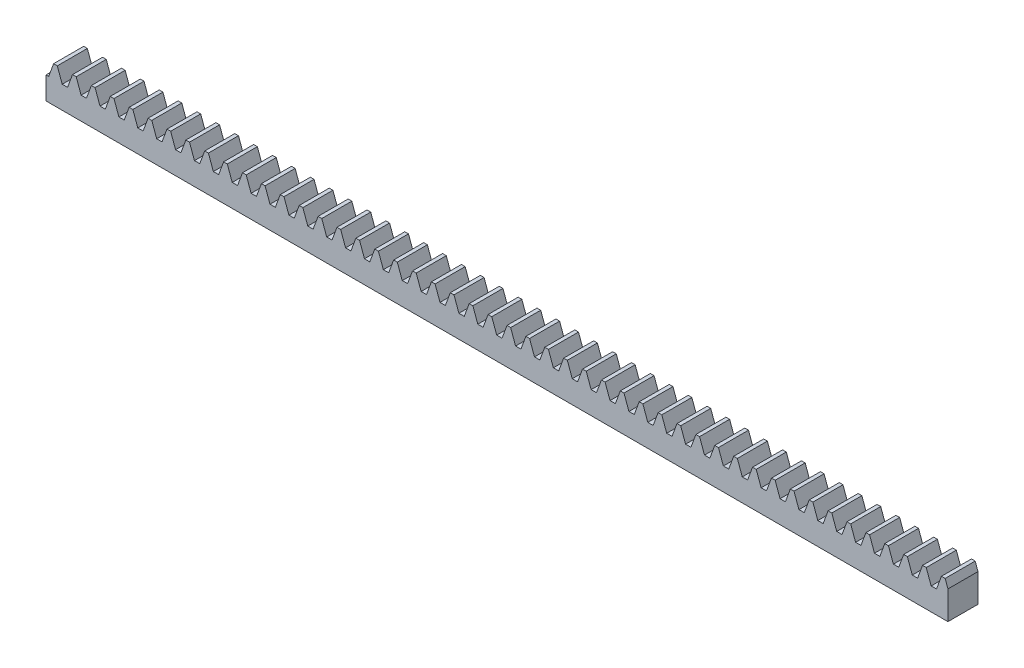
SolidWorks part; units mm, degrees
extrude "Blank" add sketch "BlankSke" against normal blind 5
sketch "BlankSke" plane through (0, 0, 0) normal (0, 0, 1) x (1, 0, 0)
  line L1 (0, 0) -> (150, 0)
  line L2 (0, 0) -> (0, 6)
  line L3 (0, 6) -> (150, 6)
  line L4 (150, 0) -> (150, 6)
  dimension "Length" = 150
  dimension "Blank_height" = 6
ref_plane "Plane1" through (0, 0, 0) normal (0, 0, 1) x (1, 0, 0)
ref_plane "Plane2" through (0, 0, 0) normal (0, 1, 0) x (1, 0, 0)
ref_plane "Plane3" through (0, 0, 0) normal (1, 0, 0) x (0, 0, -1)
sketch "HoldingSke" plane through (0, 0, 0) normal (0, 1, 0) x (1, 0, 0)
  line L0 (0, 0) -> (0.1392, 0.9903)
  line L1 (-15, 0) -> (100, 0) construction
  line L2 (0, 0) -> (-2.1039, 2.3779)
  line L3 (0, 0) -> (-11.863, 4.5341)
  line L4 (0, 0) -> (5.6657, 6.5177)
  line L5 (0, 0) -> (-23.7986, -8.8762)
  line L6 (0, 0) -> (-10.5278, -7.1032)
  line L9 (-71.009, 38.7566) -> (69.9449, 90.0596)
  line L10 (-76.2, 3.3779) -> (-71.2, 3.3779)
  line L11 (0, 0) -> (-5, 0)
  line L12 (-76.2, 101.6) -> (-76.162, 101.6)
  line L13 (24.9733, 27.94) -> (52.9518, 28.4284)
  line L14 (24.9733, 27.94) -> (24.9743, 27.94)
  line L15 (24.9733, 27.94) -> (100.4006, 29.5858)
  circle A0 centre (0, 0) radius 19.05
  circle A1 centre (0, 0) radius 2.5
  circle A2 centre (0, 0) radius 12.7
  dimension "MPH" = 5
  dimension "Diameter" = 38.1
  dimension "Num_teeth" = 49
  dimension "Pitch" = 1
  dimension "Show_teeth" = 998
  dimension "Thickness" = 12.7
  dimension "Ap" = 20
  dimension "Pitch_height" = 5
  dimension "Width" = 5
  dimension "Backlash" = 0.038
  dimension "Addendum_fac" = 1
  dimension "Dedendum_fac" = 1.25
  dimension "Clearance_fac" = 0.25
  dimension "Dedendum_add" = 0.001
  dimension "Length" = 150
  dimension "Module" = 1
sketch "TooCutSkeIll" plane through (0, 0, 0) normal (0, 0, 1) x (1, 0, 0)
  line L0 (-1.2538, 5.9737) -> (-0.5045, 3.9152)
  line L1 (-0.2687, 3.75) -> (0.2687, 3.75)
  line L2 (0.5045, 3.9152) -> (1.2538, 5.9737)
  line L3 (150, 6) -> (0, 6) construction
  line L4 (0, 0) -> (0, 64.897) construction
  line L5 (-13.208, 5) -> (12.954, 5) construction
  line L6 (0, 0) -> (150, 0) construction
  line L7 (0.8994, 5) -> (0.8994, 48.7463) construction
  line L8 (-0.8994, 5) -> (-0.8994, 48.7463) construction
  line L9 (1.2914, 6) -> (1.2914, 6.0254)
  line L10 (-1.2914, 6) -> (-1.2914, 6.0254)
  line L11 (-1.2914, 6.0254) -> (1.2914, 6.0254)
  arc A0 (0.2687, 3.75) -> (0.5045, 3.9152) centre (0.2687, 4.001) ccw
  arc A1 (-0.5045, 3.9152) -> (-0.2687, 3.75) centre (-0.2687, 4.001) ccw
  arc A2 (1.2914, 6) -> (1.2538, 5.9737) centre (1.2914, 5.96) ccw
  arc A3 (-1.2538, 5.9737) -> (-1.2914, 6) centre (-1.2914, 5.96) ccw
  dimension "Pitch_height" = 5
  dimension "Addendum_plus" = 1.0254
  dimension "Pressure_angle" = 20
  dimension "Gap_width" = 1.7988
  dimension "Dedendum" = 1.25
extrude "ToothCutIll" [suppressed] cut sketch "TooCutSkeIll" against normal through all
sketch "TooCutSkeSim" plane through (0, 0, 0) normal (0, 0, 1) x (1, 0, 0)
  line L0 (0.4444, 3.75) -> (-0.4444, 3.75)
  line L1 (1.2726, 6.0254) -> (0.4444, 3.75)
  line L2 (0, 17.4625) -> (0, 53.467) construction
  line L3 (1.2726, 6.0254) -> (-1.2726, 6.0254)
  line L6 (-1.2726, 6.0254) -> (-0.4444, 3.75)
  line L9 (-0.8994, 5) -> (0.8994, 5) construction
  line L10 (0, 0) -> (150, 0) construction
  line L11 (0.8994, 5) -> (0.8994, 53.467) construction
  line L12 (-0.8994, 5) -> (-0.8994, 53.467) construction
  dimension "Pitch_height" = 5
  dimension "Addendum_plus" = 1.0254
  dimension "Pressure_angle" = 20
  dimension "Gap_width" = 1.7988
  dimension "Dedendum" = 1.25
extrude "ToothCutSim" cut sketch "TooCutSkeSim" against normal through all
pattern_linear "TeethCuts" count 48 spacing 3.1416 along (1, 0, 0) of "ToothCutIll", "ToothCutSim"
equation "' \"Module@HoldingSke\" = 6.35"
equation "' \"Num_teeth@HoldingSke\" = 12"
equation "' \"Ap@HoldingSke\" =  20"
equation "' \"Ap@HoldingSke\" = 20"
equation "' \"Width@HoldingSke\" = 0.25 * 25.4"
equation "' \"Show_teeth@HoldingSke\" = 500"
equation "' \"Backlash@HoldingSke\" = 0.009 * 25.4"
equation "' \"Addendum_fac@HoldingSke\" = 1.0"
equation "' \"Dedendum_fac@HoldingSke\" = 1.25"
equation "' \"Dedendum_add@HoldingSke\" = 0.00005 * 25.4"
equation "' \"Clearance_fac@HoldingSke\" = 0.25"
equation "' \"Pitch_height@HoldingSke\" = 1 * 25.4"
equation "' \"Length@HoldingSke\" = 4.71 * 25.4"
equation "\"Pitch@HoldingSke\" = 1 / \"Module@HoldingSke\""
equation "\"MPH@HoldingSke\" = \"Dedendum_fac@HoldingSke\" / \"Pitch@HoldingSke\" + 2 * \"Dedendum_add@HoldingSke\" + 0.002 * 25.4"
equation "\"MPH@HoldingSke\" = ((sgn( \"MPH@HoldingSke\" - \"Pitch_height@HoldingSke\")+1)*( \"MPH@HoldingSke\" - \"Pitch_height@HoldingSke\"))/2 + \"Pitch_height@HoldingSke\""
equation "\"Blank_height@BlankSke\" = \"Pitch_height@HoldingSke\" + \"Addendum_fac@HoldingSke\"  / \"Pitch@HoldingSke\" "
equation "\"Length@BlankSke\" =  \"Length@HoldingSke\""
equation "\"Face_width@Blank\" = \"Width@HoldingSke\""
equation "\"Pressure_angle@TooCutSkeIll\" = \"Ap@HoldingSke\""
equation "\"Addendum_plus@TooCutSkeIll\" =  \"Addendum_fac@HoldingSke\"  / \"Pitch@HoldingSke\" + 0.001 *25.4"
equation "\"Dedendum@TooCutSkeIll\" = \"Dedendum_fac@HoldingSke\"  / \"Pitch@HoldingSke\""
equation "\"Pitch_height@TooCutSkeIll\" =  \"MPH@HoldingSke\""
equation "\"Gap_width@TooCutSkeIll\" = 3.14159265 / 2 / \"Pitch@HoldingSke\" + 6 * \"Backlash@HoldingSke\""
equation "\"Pressure_angle@TooCutSkeSim\" = \"Ap@HoldingSke\""
equation "\"Addendum_plus@TooCutSkeSim\" =  \"Addendum_fac@HoldingSke\"  / \"Pitch@HoldingSke\" + 0.001 * 25.4"
equation "\"Dedendum@TooCutSkeSim\" = \"Dedendum_fac@HoldingSke\"  / \"Pitch@HoldingSke\""
equation "\"Pitch_height@TooCutSkeSim\" =  \"MPH@HoldingSke\""
equation "\"Gap_width@TooCutSkeSim\" = 3.14159265 / 2 / \"Pitch@HoldingSke\" + 6 * \"Backlash@HoldingSke\""
equation "\"Root_fillet@TooCutSkeIll\" = \"Clearance_fac@HoldingSke\" / \"Pitch@HoldingSke\" + \"Dedendum_add@HoldingSke\""
equation "\"Break_rad@TooCutSkeIll\" = 0.02 / \"Pitch@HoldingSke\" * 2"
equation "\"Linear_pitch@TeethCuts\" = 3.14159265 / \"Pitch@HoldingSke\""
equation "\"Num_teeth@HoldingSke\" = int( ( \"Length@HoldingSke\" + 0 ) / (3.14159265 / \"Pitch@HoldingSke\")) + 0.9999  + 1"
equation " \"Num_teeth@TeethCuts\" = int( \"Show_teeth@HoldingSke\" ) + 1"
equation " \"Num_teeth@TeethCuts\" = ((sgn( \"Num_teeth@TeethCuts\" - \"Num_teeth@HoldingSke\" )-1)*( \"Num_teeth@TeethCuts\" - \"Num_teeth@HoldingSke\" ))/-2+ \"Num_teeth@HoldingSke\""
equation " \"Num_teeth@TeethCuts\" = ((sgn( \"Num_teeth@TeethCuts\" - 2.0)+1)*( \"Num_teeth@TeethCuts\" - 2.0))/2 +2.0"
